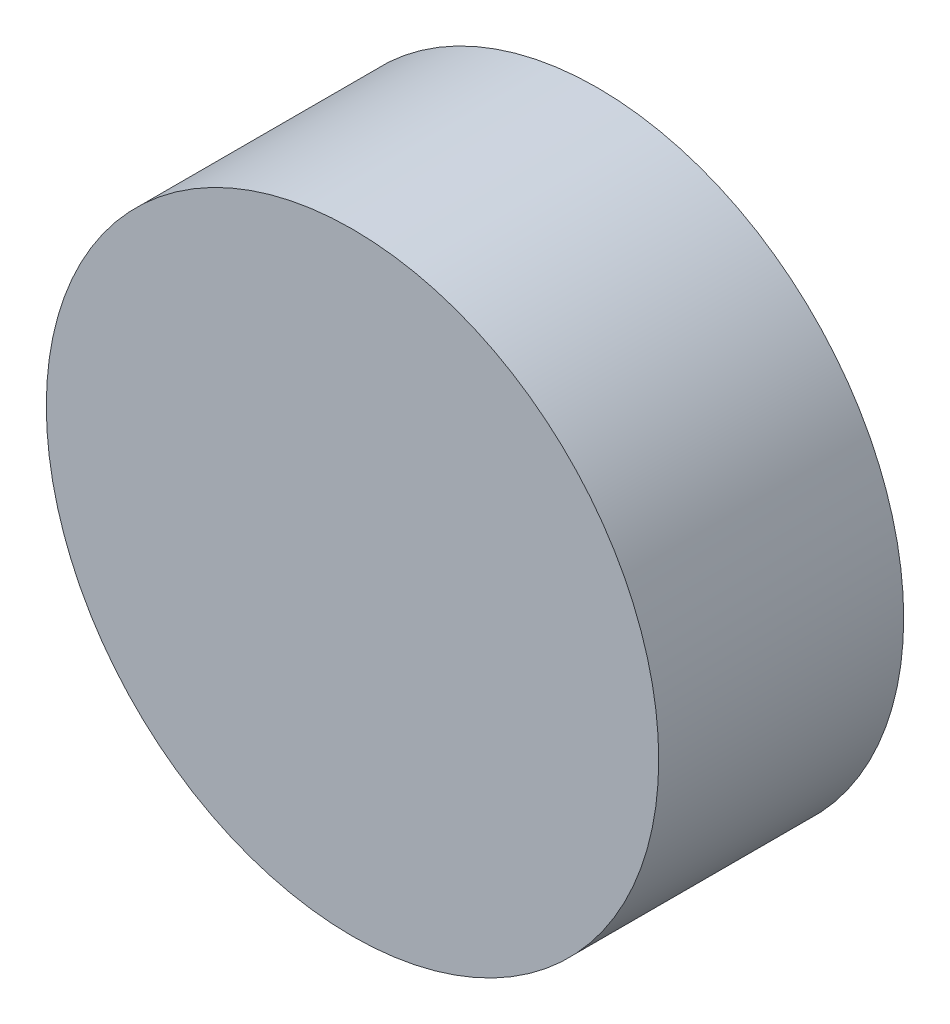
SolidWorks part; units mm, degrees
ref_plane "Front Plane" through (0, 0, 0) normal (0, 0, 1) x (1, 0, 0)
ref_plane "Top Plane" through (0, 0, 0) normal (0, 1, 0) x (1, 0, 0)
ref_plane "Right Plane" through (0, 0, 0) normal (1, 0, 0) x (0, 0, -1)
sketch "Sketch1" plane through (0, 0, 0) normal (0, 0, 1) x (1, 0, 0)
  circle A0 centre (0, 0) radius 10
extrude "OVD_QualificationExtrusion" add sketch "Sketch1" along normal blind 8
